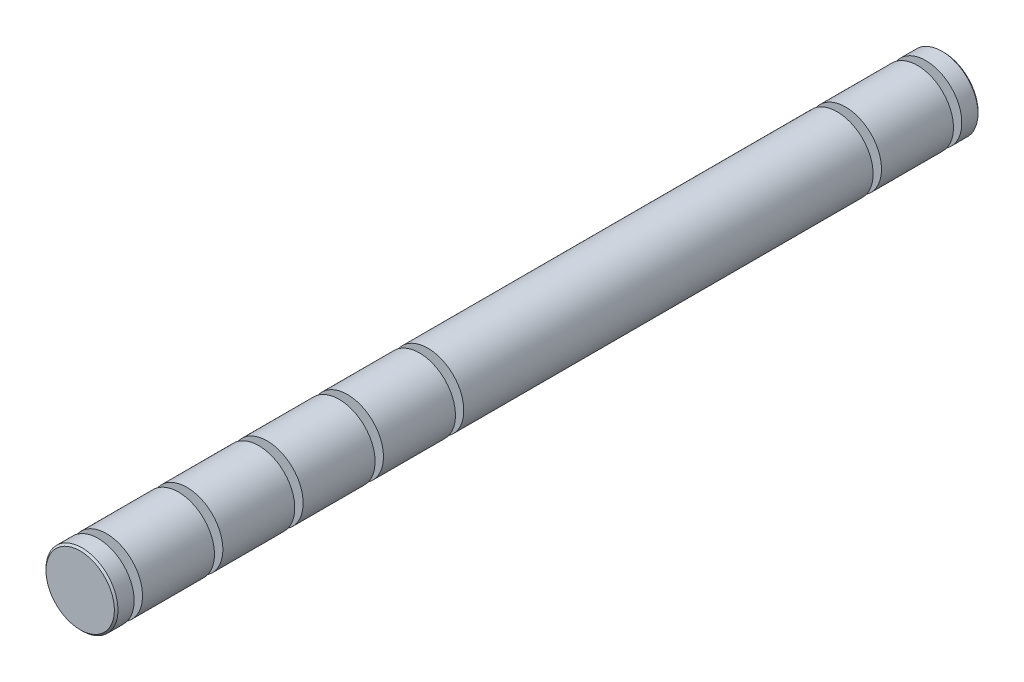
SolidWorks part; units mm, degrees
ref_plane "Front" through (0, 0, 0) normal (0, 0, 1) x (1, 0, 0)
ref_plane "Top" through (0, 0, 0) normal (0, 1, 0) x (1, 0, 0)
ref_plane "Right" through (0, 0, 0) normal (1, 0, 0) x (0, 0, -1)
sketch "Sketch1" plane through (0, 0, 0) normal (0, 0, 1) x (1, 0, 0)
  circle A0 centre (0, 0) radius 3.175
  point P3 (0, 3.175)
  dimension "dia" = 6.35
extrude "Extrude1" add sketch "Sketch1" along normal mid plane 76.2
sketch "Sketch6" plane through (0, 0, 0) normal (1, 0, 0) x (0, 0, -1)
  line L0 (-36.5125, 3.175) -> (-36.5125, 1.5875)
  line L1 (-36.5125, 1.5875) -> (-35.7759, 1.5875)
  line L2 (-35.7759, 1.5875) -> (-35.7759, 3.175)
  line L3 (-35.7759, 3.175) -> (-29.4259, 3.175)
  line L4 (-29.4259, 3.175) -> (-29.4259, 1.5875)
  line L5 (-29.4259, 1.5875) -> (-28.6893, 1.5875)
  line L6 (-28.6893, 1.5875) -> (-28.6893, 3.175)
  line L7 (-28.6893, 3.175) -> (-22.3393, 3.175)
  line L8 (-22.3393, 3.175) -> (-22.3393, 1.5875)
  line L9 (-22.3393, 1.5875) -> (-21.6027, 1.5875)
  line L10 (-21.6027, 1.5875) -> (-21.6027, 3.175)
  line L11 (-21.6027, 3.175) -> (-15.2527, 3.175)
  line L12 (-15.2527, 3.175) -> (-15.2527, 1.5875)
  line L13 (-15.2527, 1.5875) -> (-14.5161, 1.5875)
  line L14 (-14.5161, 1.5875) -> (-14.5161, 3.175)
  line L15 (-14.5161, 3.175) -> (-8.1661, 3.175)
  line L16 (-8.1661, 3.175) -> (-8.1661, 1.5875)
  line L17 (-8.1661, 1.5875) -> (-7.4295, 1.5875)
  line L18 (-7.4295, 1.5875) -> (-7.4295, 3.175)
  line L20 (-38.1, 3.175) -> (-38.1, -3.175) construction
  line L21 (-36.5125, 3.175) -> (-38.1, 3.175)
  line L22 (38.1, 3.175) -> (36.5125, 3.175)
  line L23 (36.5125, 3.175) -> (36.5125, 1.5875)
  line L24 (36.5125, 1.5875) -> (35.7759, 1.5875)
  line L25 (35.7759, 1.5875) -> (35.7759, 3.175)
  line L26 (35.7759, 3.175) -> (29.4259, 3.175)
  line L27 (29.4259, 3.175) -> (29.4259, 1.5875)
  line L28 (29.4259, 1.5875) -> (28.6893, 1.5875)
  line L29 (28.6893, 1.5875) -> (28.6893, 3.175)
  line L30 (38.1, 3.175) -> (38.1, 5.715)
  line L31 (38.1, 5.715) -> (-38.1, 5.715)
  line L32 (-38.1, 5.715) -> (-38.1, 3.175)
  line L34 (38.1, -3.175) -> (38.1, 3.175) construction
  line L35 (28.6893, 3.175) -> (-7.4295, 3.175)
  dimension "D1" = 2.54
  dimension "Groove Start" = 1.5875
  dimension "Groove Wd" = 0.7366
  dimension "Segment Lg" = 6.35
revolve "Cut-Revolve2" cut sketch "Sketch6" angle 360 mid plane about axis through (0, 0, 38.1) along (0, 0, -1)
sketch "Sketch2" plane through (0, 0, 0) normal (1, 0, 0) x (0, 0, -1)
  line L3 (-29.4259, 3.175) -> (-27.9527, 3.175) construction
  line L4 (-23.0759, 3.175) -> (-21.6027, 3.175) construction
  line L5 (-29.4259, 3.175) -> (-29.4259, 1.5875) construction
  line L6 (-21.6027, 1.5875) -> (-21.6027, 3.175) construction
  line L7 (38.1, 3.175) -> (38.1, -3.175) construction
  line L8 (3.4925, 0) -> (-3.4925, 0) construction
  point P0 (-38.1, 3.175)
  point P1 (38.1, 3.175)
  point P2 (38.1, -3.175)
  point P14 (38.1, 0)
  point P22 (-28.6893, 3.175)
  point P23 (-22.3393, 3.175)
chamfer "Chamfer1" distance 0.1588 angle 45 2 edges at (3.175, 0, -38.1) (3.175, 0, 38.1)
equation "\"D1@Chamfer1\" = \"dia@Sketch1\" * .025"
